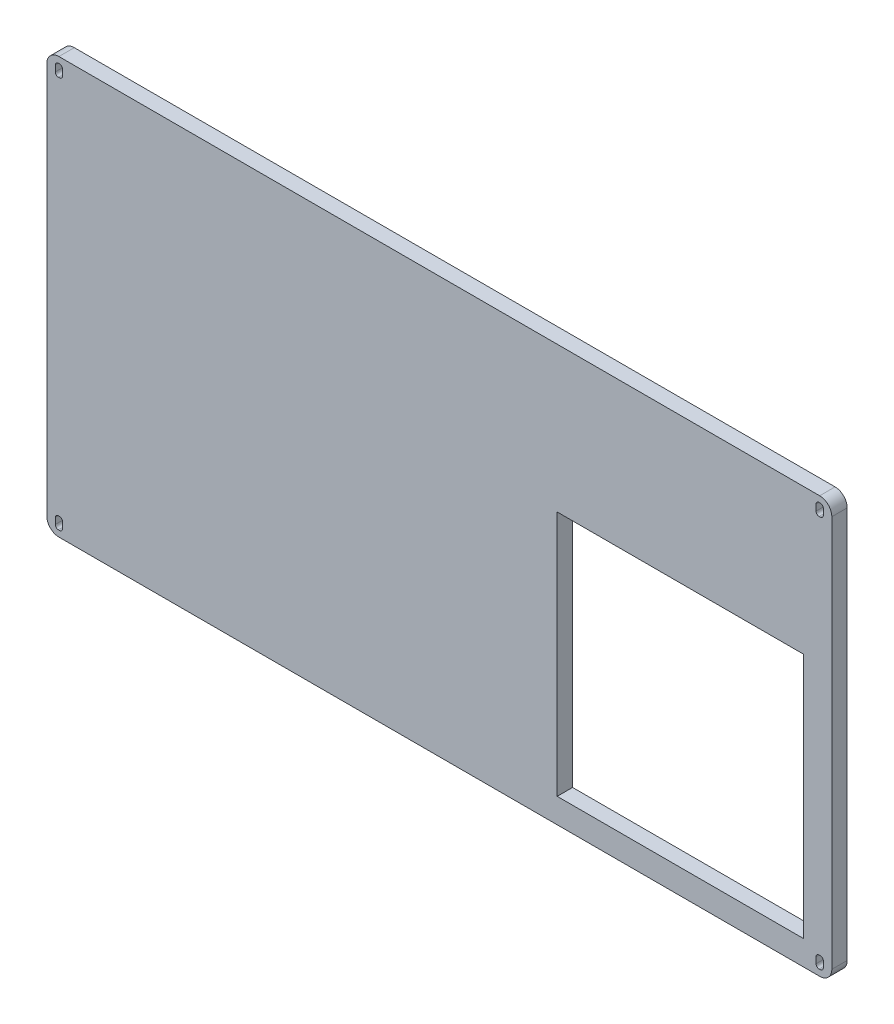
SolidWorks part; units mm, degrees
ref_plane "Front Plane" through (0, 0, 0) normal (0, 0, 1) x (1, 0, 0)
ref_plane "Top Plane" through (0, 0, 0) normal (0, 1, 0) x (1, 0, 0)
ref_plane "Right Plane" through (0, 0, 0) normal (1, 0, 0) x (0, 0, -1)
sketch "Sketch1" plane through (0, 0, 0) normal (0, 0, 1) x (1, 0, 0)
  line L0 (247.3719, -116.8652) -> (246.3719, -116.8652)
  line L1 (-390.8281, 221.5428) -> (256.8719, 221.5428)
  line L2 (-390.8281, 221.5428) -> (-390.8281, -121.8652)
  line L3 (-390.8281, -121.8652) -> (256.8719, -121.8652)
  line L4 (256.8719, 221.5428) -> (256.8719, -121.8652)
  line L5 (249.8719, -114.3652) -> (249.8719, -109.3652)
  line L6 (247.3719, -106.8652) -> (246.3719, -106.8652)
  line L7 (30.2848, -101.5271) -> (233.4848, -101.5271)
  line L8 (30.2848, -101.5271) -> (30.2848, 101.6729)
  line L9 (30.2848, 101.6729) -> (233.4848, 101.6729)
  line L10 (233.4848, -101.5271) -> (233.4848, 101.6729)
  line L11 (243.8719, -114.3652) -> (243.8719, -109.3652)
  line L12 (246.8719, -106.8652) -> (246.8719, -116.8652) construction
  line L13 (249.8719, -111.8652) -> (243.8719, -111.8652) construction
  line L14 (-380.3281, -116.8652) -> (-381.3281, -116.8652)
  line L15 (-383.8281, -114.3652) -> (-383.8281, -109.3652)
  line L16 (-380.3281, -106.8652) -> (-381.3281, -106.8652)
  line L17 (-377.8281, -114.3652) -> (-377.8281, -109.3652)
  line L18 (-380.3281, 206.5448) -> (-381.3281, 206.5448)
  line L19 (-383.8281, 209.0448) -> (-383.8281, 214.0448)
  line L20 (-380.3281, 216.5448) -> (-381.3281, 216.5448)
  line L21 (-377.8281, 209.0448) -> (-377.8281, 214.0448)
  line L22 (247.3719, 206.5448) -> (246.3719, 206.5448)
  line L23 (243.8719, 209.0448) -> (243.8719, 214.0448)
  line L24 (247.3719, 216.5448) -> (246.3719, 216.5448)
  line L25 (249.8719, 209.0448) -> (249.8719, 214.0448)
  arc A0 (247.3719, -116.8652) -> (249.8719, -114.3652) centre (247.3719, -114.3652) ccw
  arc A1 (249.8719, -109.3652) -> (247.3719, -106.8652) centre (247.3719, -109.3652) ccw
  arc A2 (246.3719, -116.8652) -> (243.8719, -114.3652) centre (246.3719, -114.3652) cw
  arc A3 (246.3719, -106.8652) -> (243.8719, -109.3652) centre (246.3719, -109.3652) ccw
  arc A4 (-381.3281, -116.8652) -> (-383.8281, -114.3652) centre (-381.3281, -114.3652) cw
  arc A5 (-381.3281, -106.8652) -> (-383.8281, -109.3652) centre (-381.3281, -109.3652) ccw
  arc A6 (-377.8281, -109.3652) -> (-380.3281, -106.8652) centre (-380.3281, -109.3652) ccw
  arc A7 (-380.3281, -116.8652) -> (-377.8281, -114.3652) centre (-380.3281, -114.3652) ccw
  arc A8 (-381.3281, 206.5448) -> (-383.8281, 209.0448) centre (-381.3281, 209.0448) cw
  arc A9 (-381.3281, 216.5448) -> (-383.8281, 214.0448) centre (-381.3281, 214.0448) ccw
  arc A10 (-377.8281, 214.0448) -> (-380.3281, 216.5448) centre (-380.3281, 214.0448) ccw
  arc A11 (-380.3281, 206.5448) -> (-377.8281, 209.0448) centre (-380.3281, 209.0448) ccw
  arc A12 (246.3719, 206.5448) -> (243.8719, 209.0448) centre (246.3719, 209.0448) cw
  arc A13 (246.3719, 216.5448) -> (243.8719, 214.0448) centre (246.3719, 214.0448) ccw
  arc A14 (249.8719, 214.0448) -> (247.3719, 216.5448) centre (247.3719, 214.0448) ccw
  arc A15 (247.3719, 206.5448) -> (249.8719, 209.0448) centre (247.3719, 209.0448) ccw
  point P22 (246.8719, -116.8652)
  point P26 (246.8719, -111.8652)
  dimension "D9" = 2.5
  dimension "D1" = 647.7
  dimension "D2" = 343.408
  dimension "D3" = 221.5428
  dimension "D4" = 256.8719
  dimension "D5" = 30.2848
  dimension "D6" = 23.3871
  dimension "D7" = 119.87
  dimension "D8" = 20.338
  dimension "D10" = 6
  dimension "D11" = 10
  dimension "D12" = 10
  dimension "D13" = 10
  dimension "D16" = 7
  dimension "D17" = 4.998
  dimension "D18" = 7
  dimension "D14" = 2
  dimension "D15" = 2
extrude "Boss-Extrude1" add sketch "Sketch1" along normal blind 12.7
fillet "Fillet1" radius 10 4 edges at (-390.8281, -121.8652, 6.35) (256.8719, -121.8652, 6.35) (256.8719, 221.5428, 6.35) (-390.8281, 221.5428, 6.35)
